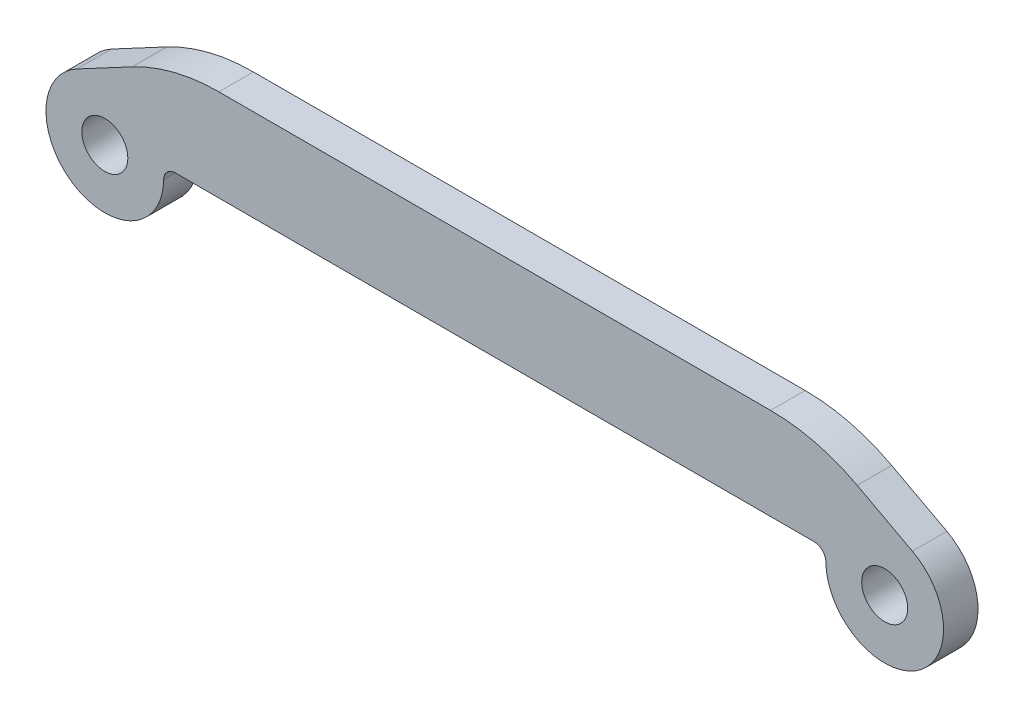
SolidWorks part; units mm, degrees
ref_plane "Front Plane" through (0, 0, 0) normal (0, 0, 1) x (1, 0, 0)
ref_plane "Top Plane" through (0, 0, 0) normal (0, 1, 0) x (1, 0, 0)
ref_plane "Right Plane" through (0, 0, 0) normal (1, 0, 0) x (0, 0, -1)
sketch "Sketch1" plane through (0, 0, 0) normal (0, 0, 1) x (1, 0, 0)
  line L0 (0, 0.8261) -> (0, -0.5691) construction
  line L1 (0.875, 0) -> (-0.875, 0)
  line L2 (-0.875, 0) -> (-1.1353, -0.1388)
  line L3 (-0.9, -0.28) -> (-0.9, -0.25)
  line L4 (-0.9, -0.25) -> (0.9, -0.25)
  line L5 (0.9, -0.28) -> (0.9, -0.25)
  line L6 (0.875, 0) -> (1.1353, -0.1388)
  arc A0 (-0.9, -0.28) -> (-1.1353, -0.1388) centre (-1.06, -0.28) cw
  circle A1 centre (-1.06, -0.28) radius 0.0625
  circle A2 centre (1.06, -0.28) radius 0.0625
  arc A3 (0.9, -0.28) -> (1.1353, -0.1388) centre (1.06, -0.28) ccw
  point P8 (-1.06, -0.44)
  point P12 (1.06, -0.44)
  point P17 (0, -0.25)
  dimension "D2" = 0.16
  dimension "D6" = 0.125
  dimension "D1" = 1.75
  dimension "D3" = 0.19
  dimension "D4" = 0.25
  dimension "D5" = 1.06
extrude "Boss-Extrude1" add sketch "Sketch1" along normal mid plane 0.0938
fillet "Fillet1" radius 0.5 2 edges at (0.875, 0, 0) (-0.875, 0, 0)
fillet "Fillet2" radius 0.032 2 edges at (0.9, -0.25, 0) (-0.9, -0.25, 0)
